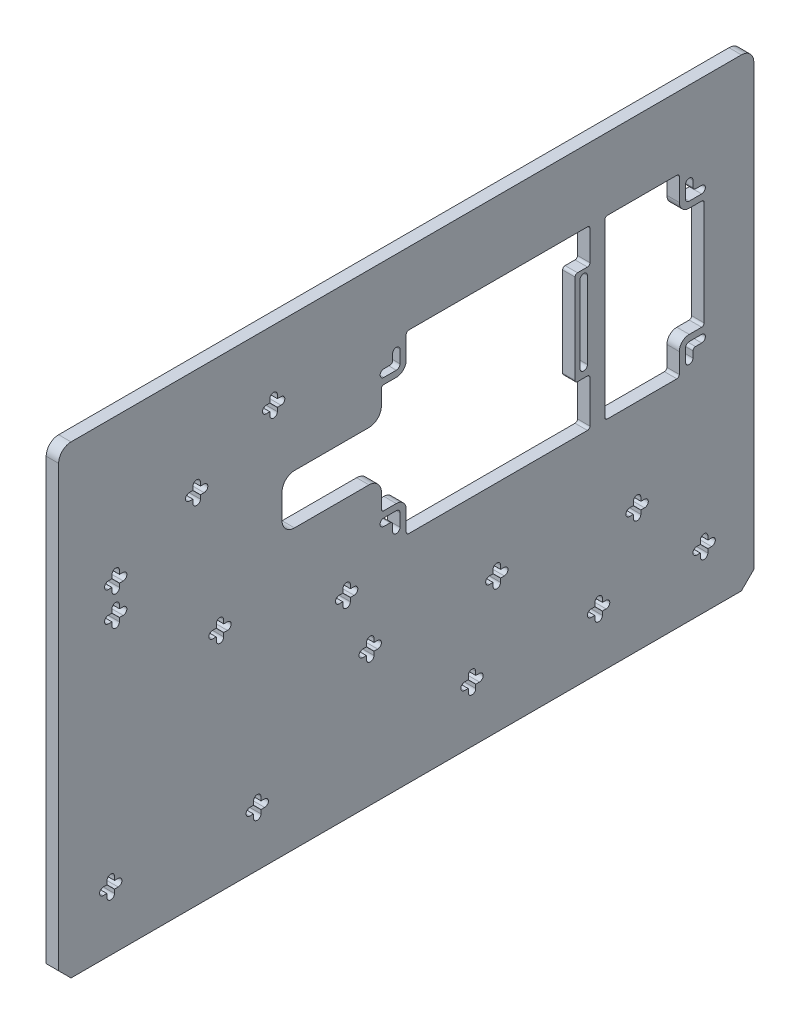
SolidWorks part; units mm, degrees
ref_plane "Front Plane" through (0, 0, 0) normal (0, 0, 1) x (1, 0, 0)
ref_plane "Top Plane" through (0, 0, 0) normal (0, 1, 0) x (1, 0, 0)
ref_plane "Right Plane" through (0, 0, 0) normal (1, 0, 0) x (0, 0, -1)
sketch "Sketch1" plane through (0, 0, 0) normal (1, 0, 0) x (0, -1, 0)
  line L0 (-12.5, 73) -> (-12.5, 69)
  line L1 (-13.5, 68) -> (-49.5, 68)
  line L2 (-50.5, 69) -> (-50.5, 73)
  line L3 (-64.5, 73) -> (-64.5, 1)
  line L4 (-7.5, 120) -> (-18.5, 120)
  line L5 (-38.5, 120) -> (-47.5, 120)
  line L6 (-47.5, 120) -> (-49.5, 120)
  line L7 (-50.5, 114) -> (-50.5, 119)
  line L8 (-6.5, 114) -> (-6.5, 119)
  line L9 (-2.5, 110) -> (1.5, 110)
  line L10 (-54.5, 110) -> (-58.5, 110)
  line L11 (-6.5, -4) -> (-6.5, -9)
  line L12 (-50.5, -4) -> (-50.5, -9)
  line L13 (-47.5, 73) -> (-16.5, 73)
  line L14 (-47.5, 70) -> (-16.5, 70)
  line L15 (-4, 119) -> (-4, 114)
  line L16 (-2.5, 112.5) -> (2.5, 112.5)
  line L17 (-1, 119) -> (-1, 116.5)
  line L18 (2.5, 115.5) -> (0, 115.5)
  line L19 (-53, 119) -> (-53, 114)
  line L20 (-59.5, 112.5) -> (-54.5, 112.5)
  line L21 (-56, 119) -> (-56, 116.5)
  line L22 (-57, 115.5) -> (-59.5, 115.5)
  line L23 (-54.5, -2.5) -> (-59.5, -2.5)
  line L24 (-53, -9) -> (-53, -4)
  line L25 (-59.5, -5.5) -> (-57, -5.5)
  line L26 (-56, -6.5) -> (-56, -9)
  line L27 (2.5, -2.5) -> (-2.5, -2.5)
  line L28 (-4, -4) -> (-4, -9)
  line L29 (-1, -9) -> (-1, -6.5)
  line L30 (2.5, -5.5) -> (0, -5.5)
  line L31 (-58.5, 80) -> (1.5, 80)
  line L32 (-49.5, -10) -> (-43.5, -10)
  line L33 (-13.5, -10) -> (-7.5, -10)
  line L34 (6.5, 1) -> (6.5, 73)
  line L35 (5.5, 74) -> (-11.5, 74)
  line L36 (-12.5, 73) -> (-12.5, 69)
  line L37 (-13.5, 68) -> (-49.5, 68)
  line L38 (-50.5, 69) -> (-50.5, 73)
  line L39 (-51.5, 74) -> (-63.5, 74)
  line L40 (-7.5, 120) -> (-28.5, 120)
  line L41 (-28.5, 120) -> (-47.5, 120)
  line L42 (-93.5, 135) -> (-93.5, -135)
  line L43 (88.5, 140) -> (-88.5, 140)
  line L44 (93.5, 135) -> (88.5, 140)
  line L45 (93.5, -135) -> (93.5, 135)
  line L46 (93.5, -135) -> (88.5, -140)
  line L47 (-47.5, 120) -> (-49.5, 120)
  line L48 (-50.5, 114) -> (-50.5, 119)
  line L49 (-6.5, 114) -> (-6.5, 119)
  line L50 (-2.5, 110) -> (5.5, 110)
  line L51 (-54.5, 110) -> (-63.5, 110)
  line L52 (-2.5, 0) -> (5.5, 0)
  line L53 (-54.5, 0) -> (-63.5, 0)
  line L54 (-6.5, -4) -> (-6.5, -9)
  line L55 (-50.5, -4) -> (-50.5, -9)
  line L56 (-47.5, 73) -> (-16.5, 73)
  line L57 (-47.5, 70) -> (-16.5, 70)
  line L58 (-4, 119) -> (-4, 114)
  line L59 (-2.5, 112.5) -> (2.5, 112.5)
  line L60 (-1, 119) -> (-1, 116.5)
  line L61 (2.5, 115.5) -> (0, 115.5)
  line L62 (-53, 119) -> (-53, 114)
  line L63 (-59.5, 112.5) -> (-54.5, 112.5)
  line L64 (-56, 119) -> (-56, 116.5)
  line L65 (-57, 115.5) -> (-59.5, 115.5)
  line L66 (-54.5, -2.5) -> (-59.5, -2.5)
  line L67 (-53, -9) -> (-53, -4)
  line L68 (-59.5, -5.5) -> (-57, -5.5)
  line L69 (-56, -6.5) -> (-56, -9)
  line L70 (2.5, -2.5) -> (-2.5, -2.5)
  line L71 (-4, -4) -> (-4, -9)
  line L72 (-1, -9) -> (-1, -6.5)
  line L73 (2.5, -5.5) -> (0, -5.5)
  line L74 (-63.5, 80) -> (5.5, 80)
  line L75 (36, -13) -> (37.45, -13)
  line L76 (37.5, -11.5) -> (37.5, -12.95)
  line L77 (36, -16) -> (37.45, -16)
  line L78 (37.5, -17.5) -> (37.5, -16.05)
  line L79 (40.5, -17.5) -> (40.5, -16.05)
  line L80 (40.55, -16) -> (42, -16)
  line L81 (40.55, -13) -> (42, -13)
  line L82 (40.5, -12.95) -> (40.5, -11.5)
  line L83 (68, 28) -> (69.45, 28)
  line L84 (69.5, 29.5) -> (69.5, 28.05)
  line L85 (68, 25) -> (69.45, 25)
  line L86 (69.5, 23.5) -> (69.5, 24.95)
  line L87 (72.5, 23.5) -> (72.5, 24.95)
  line L88 (72.55, 25) -> (74, 25)
  line L89 (72.55, 28) -> (74, 28)
  line L90 (72.5, 28.05) -> (72.5, 29.5)
  line L91 (17, -21) -> (17, -22.45)
  line L92 (18.5, -22.5) -> (17.05, -22.5)
  line L93 (14, -21) -> (14, -22.45)
  line L94 (12.5, -22.5) -> (13.95, -22.5)
  line L95 (12.5, -25.5) -> (13.95, -25.5)
  line L96 (14, -25.55) -> (14, -27)
  line L97 (17, -25.55) -> (17, -27)
  line L98 (17.05, -25.5) -> (18.5, -25.5)
  line L99 (73, -57) -> (73, -58.45)
  line L100 (74.5, -58.5) -> (73.05, -58.5)
  line L101 (70, -57) -> (70, -58.45)
  line L102 (68.5, -58.5) -> (69.95, -58.5)
  line L103 (68.5, -61.5) -> (69.95, -61.5)
  line L104 (70, -61.55) -> (70, -63)
  line L105 (73, -61.55) -> (73, -63)
  line L106 (73.05, -61.5) -> (74.5, -61.5)
  line L107 (40.5, 94.5) -> (41.95, 94.5)
  line L108 (42, 96) -> (42, 94.55)
  line L109 (40.5, 91.5) -> (41.95, 91.5)
  line L110 (42, 90) -> (42, 91.45)
  line L111 (45, 90) -> (45, 91.45)
  line L112 (45.05, 91.5) -> (46.5, 91.5)
  line L113 (45.05, 94.5) -> (46.5, 94.5)
  line L114 (45, 94.55) -> (45, 96)
  line L115 (67.5, 121.5) -> (68.95, 121.5)
  line L116 (69, 123) -> (69, 121.55)
  line L117 (67.5, 118.5) -> (68.95, 118.5)
  line L118 (69, 117) -> (69, 118.45)
  line L119 (72, 117) -> (72, 118.45)
  line L120 (72.05, 118.5) -> (73.5, 118.5)
  line L121 (72.05, 121.5) -> (73.5, 121.5)
  line L122 (72, 121.55) -> (72, 123)
  line L123 (-34.5, -120) -> (-34.5, -118.55)
  line L124 (-33, -118.5) -> (-34.45, -118.5)
  line L125 (-37.5, -120) -> (-37.5, -118.55)
  line L126 (-39, -118.5) -> (-37.55, -118.5)
  line L127 (-39, -115.5) -> (-37.55, -115.5)
  line L128 (-37.5, -115.45) -> (-37.5, -114)
  line L129 (-34.5, -115.45) -> (-34.5, -114)
  line L130 (-34.45, -115.5) -> (-33, -115.5)
  line L131 (-22.5, -120) -> (-22.5, -118.55)
  line L132 (-21, -118.5) -> (-22.45, -118.5)
  line L133 (-25.5, -120) -> (-25.5, -118.55)
  line L134 (-27, -118.5) -> (-25.55, -118.5)
  line L135 (-27, -115.5) -> (-25.55, -115.5)
  line L136 (-25.5, -115.45) -> (-25.5, -114)
  line L137 (-22.5, -115.45) -> (-22.5, -114)
  line L138 (-22.45, -115.5) -> (-21, -115.5)
  line L139 (36, 38) -> (37.45, 38)
  line L140 (37.5, 39.5) -> (37.5, 38.05)
  line L141 (36, 35) -> (37.45, 35)
  line L142 (37.5, 33.5) -> (37.5, 34.95)
  line L143 (40.5, 33.5) -> (40.5, 34.95)
  line L144 (40.55, 35) -> (42, 35)
  line L145 (40.55, 38) -> (42, 38)
  line L146 (40.5, 38.05) -> (40.5, 39.5)
  line L147 (68, 79) -> (69.45, 79)
  line L148 (69.5, 80.5) -> (69.5, 79.05)
  line L149 (68, 76) -> (69.45, 76)
  line L150 (69.5, 74.5) -> (69.5, 75.95)
  line L151 (72.5, 74.5) -> (72.5, 75.95)
  line L152 (72.55, 76) -> (74, 76)
  line L153 (72.55, 79) -> (74, 79)
  line L154 (72.5, 79.05) -> (72.5, 80.5)
  line L155 (-88.5, -140) -> (88.5, -140)
  line L156 (3.75, -72) -> (3.75, -73.45)
  line L157 (5.25, -73.5) -> (3.8, -73.5)
  line L158 (0.75, -72) -> (0.75, -73.45)
  line L159 (-0.75, -73.5) -> (0.7, -73.5)
  line L160 (-0.75, -76.5) -> (0.7, -76.5)
  line L161 (0.75, -76.55) -> (0.75, -78)
  line L162 (3.75, -76.55) -> (3.75, -78)
  line L163 (3.8, -76.5) -> (5.25, -76.5)
  line L164 (71.25, -116) -> (71.25, -117.45)
  line L165 (72.75, -117.5) -> (71.3, -117.5)
  line L166 (68.25, -116) -> (68.25, -117.45)
  line L167 (66.75, -117.5) -> (68.2, -117.5)
  line L168 (66.75, -120.5) -> (68.2, -120.5)
  line L169 (68.25, -120.55) -> (68.25, -122)
  line L170 (71.25, -120.55) -> (71.25, -122)
  line L171 (71.3, -120.5) -> (72.75, -120.5)
  line L172 (-38.5, -15) -> (-38.5, -45)
  line L173 (-18.5, -15) -> (-18.5, -45)
  line L174 (-23.5, -50) -> (-33.5, -50)
  line L175 (-68.5, -54.9) -> (-67.05, -54.9)
  line L176 (-67, -56.4) -> (-67, -54.95)
  line L177 (-68.5, -51.9) -> (-67.05, -51.9)
  line L178 (-67, -50.4) -> (-67, -51.85)
  line L179 (-64, -50.4) -> (-64, -51.85)
  line L180 (-63.95, -51.9) -> (-62.5, -51.9)
  line L181 (-63.95, -54.9) -> (-62.5, -54.9)
  line L182 (-64, -54.95) -> (-64, -56.4)
  line L183 (-53.5, -85.9) -> (-52.05, -85.9)
  line L184 (-52, -87.4) -> (-52, -85.95)
  line L185 (-53.5, -82.9) -> (-52.05, -82.9)
  line L186 (-52, -81.4) -> (-52, -82.85)
  line L187 (-49, -81.4) -> (-49, -82.85)
  line L188 (-48.95, -82.9) -> (-47.5, -82.9)
  line L189 (-48.95, -85.9) -> (-47.5, -85.9)
  line L190 (-49, -85.95) -> (-49, -87.4)
  line L191 (-64.5, 81) -> (-64.5, 109)
  line L192 (6.5, 81) -> (6.5, 109)
  line L193 (0, -140) -> (0, 140) construction
  line L194 (-93.5, 0) -> (93.5, 0) construction
  arc A0 (-16.5, 70) -> (-16.5, 73) centre (-16.5, 71.5) ccw
  arc A1 (-47.5, 73) -> (-47.5, 70) centre (-47.5, 71.5) ccw
  arc A2 (-7.5, -10) -> (-6.5, -9) centre (-7.5, -9) ccw
  arc A3 (-50.5, -9) -> (-49.5, -10) centre (-49.5, -9) ccw
  arc A4 (-11.5, 74) -> (-12.5, 73) centre (-11.5, 73) ccw
  arc A5 (-13.5, 68) -> (-12.5, 69) centre (-13.5, 69) ccw
  arc A6 (-50.5, 69) -> (-49.5, 68) centre (-49.5, 69) ccw
  arc A7 (-50.5, 73) -> (-51.5, 74) centre (-51.5, 73) ccw
  arc A8 (-54.5, 112.5) -> (-53, 114) centre (-54.5, 114) ccw
  arc A9 (-4, 114) -> (-2.5, 112.5) centre (-2.5, 114) ccw
  arc A10 (-2.5, -2.5) -> (-4, -4) centre (-2.5, -4) ccw
  arc A11 (-53, -4) -> (-54.5, -2.5) centre (-54.5, -4) ccw
  arc A12 (-6.5, 114) -> (-2.5, 110) centre (-2.5, 114) ccw
  arc A13 (-54.5, 110) -> (-50.5, 114) centre (-54.5, 114) ccw
  arc A14 (-49.5, 120) -> (-50.5, 119) centre (-49.5, 119) ccw
  arc A15 (-6.5, 119) -> (-7.5, 120) centre (-7.5, 119) ccw
  arc A16 (-2.5, 0) -> (-6.5, -4) centre (-2.5, -4) ccw
  arc A17 (-50.5, -4) -> (-54.5, 0) centre (-54.5, -4) ccw
  arc A18 (-1, 119) -> (-4, 119) centre (-2.5, 119) ccw
  arc A19 (2.5, 112.5) -> (2.5, 115.5) centre (2.5, 114) ccw
  arc A20 (-53, 119) -> (-56, 119) centre (-54.5, 119) ccw
  arc A21 (-59.5, 115.5) -> (-59.5, 112.5) centre (-59.5, 114) ccw
  arc A22 (2.5, -5.5) -> (2.5, -2.5) centre (2.5, -4) ccw
  arc A23 (-4, -9) -> (-1, -9) centre (-2.5, -9) ccw
  arc A24 (-59.5, -2.5) -> (-59.5, -5.5) centre (-59.5, -4) ccw
  arc A25 (-56, -9) -> (-53, -9) centre (-54.5, -9) ccw
  arc A26 (-1, 116.5) -> (0, 115.5) centre (0, 116.5) ccw
  arc A27 (-57, 115.5) -> (-56, 116.5) centre (-57, 116.5) ccw
  arc A28 (-56, -6.5) -> (-57, -5.5) centre (-57, -6.5) ccw
  arc A29 (0, -5.5) -> (-1, -6.5) centre (0, -6.5) ccw
  arc A30 (-16.5, 70) -> (-16.5, 73) centre (-16.5, 71.5) ccw
  arc A31 (-47.5, 73) -> (-47.5, 70) centre (-47.5, 71.5) ccw
  arc A32 (-38.5, -15) -> (-43.5, -10) centre (-43.5, -15) ccw
  arc A33 (-13.5, -10) -> (-18.5, -15) centre (-13.5, -15) ccw
  arc A34 (-7.5, -10) -> (-6.5, -9) centre (-7.5, -9) ccw
  arc A35 (-50.5, -9) -> (-49.5, -10) centre (-49.5, -9) ccw
  arc A36 (6.5, 73) -> (5.5, 74) centre (5.5, 73) ccw
  arc A37 (5.5, 0) -> (6.5, 1) centre (5.5, 1) ccw
  arc A38 (-11.5, 74) -> (-12.5, 73) centre (-11.5, 73) ccw
  arc A39 (-13.5, 68) -> (-12.5, 69) centre (-13.5, 69) ccw
  arc A40 (-50.5, 69) -> (-49.5, 68) centre (-49.5, 69) ccw
  arc A41 (-50.5, 73) -> (-51.5, 74) centre (-51.5, 73) ccw
  arc A42 (-63.5, 74) -> (-64.5, 73) centre (-63.5, 73) ccw
  arc A43 (-93.5, -135) -> (-88.5, -140) centre (-88.5, -135) ccw
  arc A44 (-88.5, 140) -> (-93.5, 135) centre (-88.5, 135) ccw
  arc A45 (-54.5, 112.5) -> (-53, 114) centre (-54.5, 114) ccw
  arc A46 (-4, 114) -> (-2.5, 112.5) centre (-2.5, 114) ccw
  arc A47 (-2.5, -2.5) -> (-4, -4) centre (-2.5, -4) ccw
  arc A48 (-53, -4) -> (-54.5, -2.5) centre (-54.5, -4) ccw
  arc A49 (-6.5, 114) -> (-2.5, 110) centre (-2.5, 114) ccw
  arc A50 (-54.5, 110) -> (-50.5, 114) centre (-54.5, 114) ccw
  arc A51 (-49.5, 120) -> (-50.5, 119) centre (-49.5, 119) ccw
  arc A52 (-6.5, 119) -> (-7.5, 120) centre (-7.5, 119) ccw
  arc A53 (-63.5, 110) -> (-64.5, 109) centre (-63.5, 109) ccw
  arc A54 (-2.5, 0) -> (-6.5, -4) centre (-2.5, -4) ccw
  arc A55 (-50.5, -4) -> (-54.5, 0) centre (-54.5, -4) ccw
  arc A56 (-64.5, 1) -> (-63.5, 0) centre (-63.5, 1) ccw
  arc A57 (-1, 119) -> (-4, 119) centre (-2.5, 119) ccw
  arc A58 (2.5, 112.5) -> (2.5, 115.5) centre (2.5, 114) ccw
  arc A59 (-53, 119) -> (-56, 119) centre (-54.5, 119) ccw
  arc A60 (-59.5, 115.5) -> (-59.5, 112.5) centre (-59.5, 114) ccw
  arc A61 (2.5, -5.5) -> (2.5, -2.5) centre (2.5, -4) ccw
  arc A62 (-4, -9) -> (-1, -9) centre (-2.5, -9) ccw
  arc A63 (-59.5, -2.5) -> (-59.5, -5.5) centre (-59.5, -4) ccw
  arc A64 (-56, -9) -> (-53, -9) centre (-54.5, -9) ccw
  arc A65 (-1, 116.5) -> (0, 115.5) centre (0, 116.5) ccw
  arc A66 (-57, 115.5) -> (-56, 116.5) centre (-57, 116.5) ccw
  arc A67 (-56, -6.5) -> (-57, -5.5) centre (-57, -6.5) ccw
  arc A68 (0, -5.5) -> (-1, -6.5) centre (0, -6.5) ccw
  arc A69 (5.5, 80) -> (6.5, 81) centre (5.5, 81) ccw
  arc A70 (36, -13) -> (36, -16) centre (36, -14.5) ccw
  arc A71 (42, -16) -> (42, -13) centre (42, -14.5) ccw
  arc A72 (37.5, -17.5) -> (40.5, -17.5) centre (39, -17.5) ccw
  arc A73 (40.5, -11.5) -> (37.5, -11.5) centre (39, -11.5) ccw
  arc A74 (37.45, -13) -> (37.5, -12.95) centre (37.45, -12.95) ccw
  arc A75 (37.5, -16.05) -> (37.45, -16) centre (37.45, -16.05) ccw
  arc A76 (40.55, -16) -> (40.5, -16.05) centre (40.55, -16.05) ccw
  arc A77 (40.5, -12.95) -> (40.55, -13) centre (40.55, -12.95) ccw
  arc A78 (68, 28) -> (68, 25) centre (68, 26.5) ccw
  arc A79 (74, 25) -> (74, 28) centre (74, 26.5) ccw
  arc A80 (69.5, 23.5) -> (72.5, 23.5) centre (71, 23.5) ccw
  arc A81 (72.5, 29.5) -> (69.5, 29.5) centre (71, 29.5) ccw
  arc A82 (69.45, 28) -> (69.5, 28.05) centre (69.45, 28.05) ccw
  arc A83 (69.5, 24.95) -> (69.45, 25) centre (69.45, 24.95) ccw
  arc A84 (72.55, 25) -> (72.5, 24.95) centre (72.55, 24.95) ccw
  arc A85 (72.5, 28.05) -> (72.55, 28) centre (72.55, 28.05) ccw
  arc A86 (17, -21) -> (14, -21) centre (15.5, -21) ccw
  arc A87 (14, -27) -> (17, -27) centre (15.5, -27) ccw
  arc A88 (12.5, -22.5) -> (12.5, -25.5) centre (12.5, -24) ccw
  arc A89 (18.5, -25.5) -> (18.5, -22.5) centre (18.5, -24) ccw
  arc A90 (17, -22.45) -> (17.05, -22.5) centre (17.05, -22.45) ccw
  arc A91 (13.95, -22.5) -> (14, -22.45) centre (13.95, -22.45) ccw
  arc A92 (14, -25.55) -> (13.95, -25.5) centre (13.95, -25.55) ccw
  arc A93 (17.05, -25.5) -> (17, -25.55) centre (17.05, -25.55) ccw
  arc A94 (73, -57) -> (70, -57) centre (71.5, -57) ccw
  arc A95 (70, -63) -> (73, -63) centre (71.5, -63) ccw
  arc A96 (68.5, -58.5) -> (68.5, -61.5) centre (68.5, -60) ccw
  arc A97 (74.5, -61.5) -> (74.5, -58.5) centre (74.5, -60) ccw
  arc A98 (73, -58.45) -> (73.05, -58.5) centre (73.05, -58.45) ccw
  arc A99 (69.95, -58.5) -> (70, -58.45) centre (69.95, -58.45) ccw
  arc A100 (70, -61.55) -> (69.95, -61.5) centre (69.95, -61.55) ccw
  arc A101 (73.05, -61.5) -> (73, -61.55) centre (73.05, -61.55) ccw
  arc A102 (40.5, 94.5) -> (40.5, 91.5) centre (40.5, 93) ccw
  arc A103 (46.5, 91.5) -> (46.5, 94.5) centre (46.5, 93) ccw
  arc A104 (42, 90) -> (45, 90) centre (43.5, 90) ccw
  arc A105 (45, 96) -> (42, 96) centre (43.5, 96) ccw
  arc A106 (41.95, 94.5) -> (42, 94.55) centre (41.95, 94.55) ccw
  arc A107 (42, 91.45) -> (41.95, 91.5) centre (41.95, 91.45) ccw
  arc A108 (45.05, 91.5) -> (45, 91.45) centre (45.05, 91.45) ccw
  arc A109 (45, 94.55) -> (45.05, 94.5) centre (45.05, 94.55) ccw
  arc A110 (67.5, 121.5) -> (67.5, 118.5) centre (67.5, 120) ccw
  arc A111 (73.5, 118.5) -> (73.5, 121.5) centre (73.5, 120) ccw
  arc A112 (69, 117) -> (72, 117) centre (70.5, 117) ccw
  arc A113 (72, 123) -> (69, 123) centre (70.5, 123) ccw
  arc A114 (68.95, 121.5) -> (69, 121.55) centre (68.95, 121.55) ccw
  arc A115 (69, 118.45) -> (68.95, 118.5) centre (68.95, 118.45) ccw
  arc A116 (72.05, 118.5) -> (72, 118.45) centre (72.05, 118.45) ccw
  arc A117 (72, 121.55) -> (72.05, 121.5) centre (72.05, 121.55) ccw
  arc A118 (-37.5, -120) -> (-34.5, -120) centre (-36, -120) ccw
  arc A119 (-34.5, -114) -> (-37.5, -114) centre (-36, -114) ccw
  arc A120 (-39, -115.5) -> (-39, -118.5) centre (-39, -117) ccw
  arc A121 (-33, -118.5) -> (-33, -115.5) centre (-33, -117) ccw
  arc A122 (-34.45, -118.5) -> (-34.5, -118.55) centre (-34.45, -118.55) ccw
  arc A123 (-37.5, -118.55) -> (-37.55, -118.5) centre (-37.55, -118.55) ccw
  arc A124 (-37.55, -115.5) -> (-37.5, -115.45) centre (-37.55, -115.45) ccw
  arc A125 (-34.5, -115.45) -> (-34.45, -115.5) centre (-34.45, -115.45) ccw
  arc A126 (-25.5, -120) -> (-22.5, -120) centre (-24, -120) ccw
  arc A127 (-22.5, -114) -> (-25.5, -114) centre (-24, -114) ccw
  arc A128 (-27, -115.5) -> (-27, -118.5) centre (-27, -117) ccw
  arc A129 (-21, -118.5) -> (-21, -115.5) centre (-21, -117) ccw
  arc A130 (-22.45, -118.5) -> (-22.5, -118.55) centre (-22.45, -118.55) ccw
  arc A131 (-25.5, -118.55) -> (-25.55, -118.5) centre (-25.55, -118.55) ccw
  arc A132 (-25.55, -115.5) -> (-25.5, -115.45) centre (-25.55, -115.45) ccw
  arc A133 (-22.5, -115.45) -> (-22.45, -115.5) centre (-22.45, -115.45) ccw
  arc A134 (36, 38) -> (36, 35) centre (36, 36.5) ccw
  arc A135 (42, 35) -> (42, 38) centre (42, 36.5) ccw
  arc A136 (37.5, 33.5) -> (40.5, 33.5) centre (39, 33.5) ccw
  arc A137 (40.5, 39.5) -> (37.5, 39.5) centre (39, 39.5) ccw
  arc A138 (37.45, 38) -> (37.5, 38.05) centre (37.45, 38.05) ccw
  arc A139 (37.5, 34.95) -> (37.45, 35) centre (37.45, 34.95) ccw
  arc A140 (40.55, 35) -> (40.5, 34.95) centre (40.55, 34.95) ccw
  arc A141 (40.5, 38.05) -> (40.55, 38) centre (40.55, 38.05) ccw
  arc A142 (68, 79) -> (68, 76) centre (68, 77.5) ccw
  arc A143 (74, 76) -> (74, 79) centre (74, 77.5) ccw
  arc A144 (69.5, 74.5) -> (72.5, 74.5) centre (71, 74.5) ccw
  arc A145 (72.5, 80.5) -> (69.5, 80.5) centre (71, 80.5) ccw
  arc A146 (69.45, 79) -> (69.5, 79.05) centre (69.45, 79.05) ccw
  arc A147 (69.5, 75.95) -> (69.45, 76) centre (69.45, 75.95) ccw
  arc A148 (72.55, 76) -> (72.5, 75.95) centre (72.55, 75.95) ccw
  arc A149 (72.5, 79.05) -> (72.55, 79) centre (72.55, 79.05) ccw
  arc A150 (3.75, -72) -> (0.75, -72) centre (2.25, -72) ccw
  arc A151 (0.75, -78) -> (3.75, -78) centre (2.25, -78) ccw
  arc A152 (-0.75, -73.5) -> (-0.75, -76.5) centre (-0.75, -75) ccw
  arc A153 (5.25, -76.5) -> (5.25, -73.5) centre (5.25, -75) ccw
  arc A154 (3.75, -73.45) -> (3.8, -73.5) centre (3.8, -73.45) ccw
  arc A155 (0.7, -73.5) -> (0.75, -73.45) centre (0.7, -73.45) ccw
  arc A156 (0.75, -76.55) -> (0.7, -76.5) centre (0.7, -76.55) ccw
  arc A157 (3.8, -76.5) -> (3.75, -76.55) centre (3.8, -76.55) ccw
  arc A158 (71.25, -116) -> (68.25, -116) centre (69.75, -116) ccw
  arc A159 (66.75, -117.5) -> (66.75, -120.5) centre (66.75, -119) ccw
  arc A160 (72.75, -120.5) -> (72.75, -117.5) centre (72.75, -119) ccw
  arc A161 (71.25, -117.45) -> (71.3, -117.5) centre (71.3, -117.45) ccw
  arc A162 (68.2, -117.5) -> (68.25, -117.45) centre (68.2, -117.45) ccw
  arc A163 (68.25, -120.55) -> (68.2, -120.5) centre (68.2, -120.55) ccw
  arc A164 (71.3, -120.5) -> (71.25, -120.55) centre (71.3, -120.55) ccw
  arc A165 (68.25, -122) -> (71.25, -122) centre (69.75, -122) ccw
  arc A166 (-23.5, -50) -> (-18.5, -45) centre (-23.5, -45) ccw
  arc A167 (-38.5, -45) -> (-33.5, -50) centre (-33.5, -45) ccw
  arc A168 (-68.5, -51.9) -> (-68.5, -54.9) centre (-68.5, -53.4) ccw
  arc A169 (-62.5, -54.9) -> (-62.5, -51.9) centre (-62.5, -53.4) ccw
  arc A170 (-64, -50.4) -> (-67, -50.4) centre (-65.5, -50.4) ccw
  arc A171 (-67, -56.4) -> (-64, -56.4) centre (-65.5, -56.4) ccw
  arc A172 (-67, -54.95) -> (-67.05, -54.9) centre (-67.05, -54.95) ccw
  arc A173 (-67.05, -51.9) -> (-67, -51.85) centre (-67.05, -51.85) ccw
  arc A174 (-64, -51.85) -> (-63.95, -51.9) centre (-63.95, -51.85) ccw
  arc A175 (-63.95, -54.9) -> (-64, -54.95) centre (-63.95, -54.95) ccw
  arc A176 (-53.5, -82.9) -> (-53.5, -85.9) centre (-53.5, -84.4) ccw
  arc A177 (-47.5, -85.9) -> (-47.5, -82.9) centre (-47.5, -84.4) ccw
  arc A178 (-49, -81.4) -> (-52, -81.4) centre (-50.5, -81.4) ccw
  arc A179 (-52, -87.4) -> (-49, -87.4) centre (-50.5, -87.4) ccw
  arc A180 (-52, -85.95) -> (-52.05, -85.9) centre (-52.05, -85.95) ccw
  arc A181 (-52.05, -82.9) -> (-52, -82.85) centre (-52.05, -82.85) ccw
  arc A182 (-49, -82.85) -> (-48.95, -82.9) centre (-48.95, -82.85) ccw
  arc A183 (-48.95, -85.9) -> (-49, -85.95) centre (-48.95, -85.95) ccw
  arc A184 (-64.5, 81) -> (-63.5, 80) centre (-63.5, 81) ccw
  arc A185 (6.5, 109) -> (5.5, 110) centre (5.5, 109) ccw
extrude "Boss-Extrude1" add sketch "Sketch1" along normal mid plane 5 contours L43 A44 L42 A43 L155 L46 L45 L44 A185 L192 A69 L74 L31 A184 L191 A53 L51 L10 A13 L7 A14 L6 L5 L41 L40 L4 A15 L8 A12 L9 L50 A167 L172 A32 L32 A3 L12 A17 L53 A56 L3 A42 L39 A7 L2 A6 L1 A5
